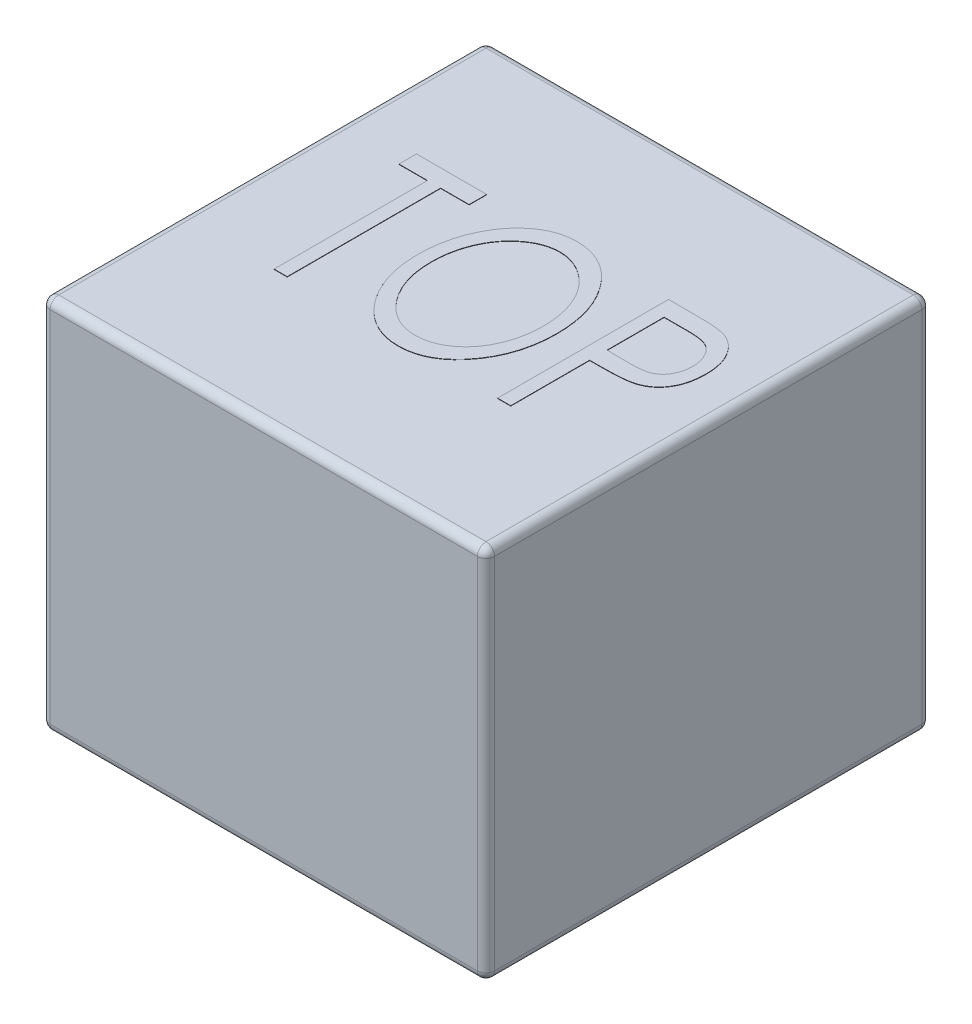
SolidWorks part; units mm, degrees
material "Nylon 101"
ref_plane "Front Plane" through (0, 0, 0) normal (0, 0, 1) x (1, 0, 0)
ref_plane "Top Plane" through (0, 0, 0) normal (0, 1, 0) x (1, 0, 0)
ref_plane "Right Plane" through (0, 0, 0) normal (1, 0, 0) x (0, 0, -1)
sketch "Sketch1" plane through (0, 0, 0) normal (0, 1, 0) x (1, 0, 0)
  line L1 (-165.1, -165.1) -> (165.1, -165.1)
  line L2 (-165.1, -165.1) -> (-165.1, 165.1)
  line L3 (-165.1, 165.1) -> (165.1, 165.1)
  line L4 (165.1, -165.1) -> (165.1, 165.1)
  line L5 (-165.1, -165.1) -> (165.1, 165.1) construction
  line L6 (-165.1, 165.1) -> (165.1, -165.1) construction
  point P0 (0, 0)
  dimension "D1" = 330.2
extrude "Boss-Extrude1" add sketch "Sketch1" along normal mid plane 279.4
fillet "Fillet1" radius 6.35 12 edges at (-165.1, -139.7, 0) (-165.1, 0, -165.1) (0, -139.7, -165.1) (165.1, 0, -165.1) (165.1, -139.7, 0) (-165.1, 139.7, 0) (0, 139.7, -165.1) (165.1, 139.7, 0) (-165.1, 0, 165.1) (0, 139.7, 165.1) (165.1, 0, 165.1) (0, -139.7, 165.1)
shell "Shell1" thickness 2.54
sketch "Sketch2" plane through (0, 139.7, 0) normal (0, 1, 0) x (1, 0, 0)
  text T0 "TOP" font "Century Gothic" height 127
extrude "Boss-Extrude2" add sketch "Sketch2" along normal blind 0.254
